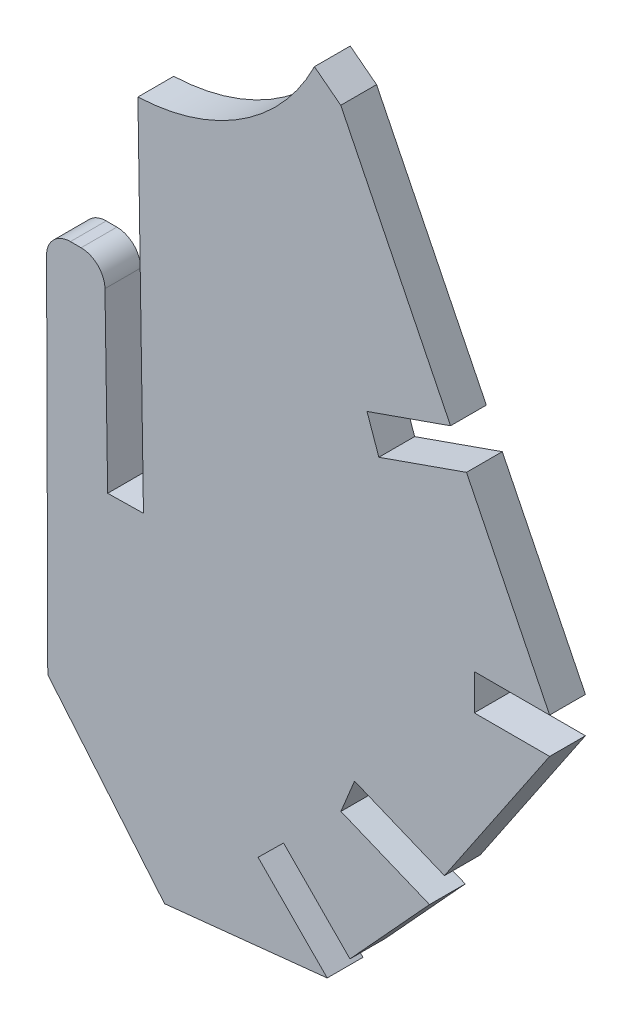
SolidWorks part; units mm, degrees
ref_plane "Front" through (0, 0, 0) normal (0, 0, 1) x (1, 0, 0)
ref_plane "Top" through (0, 0, 0) normal (0, 1, 0) x (1, 0, 0)
ref_plane "Right" through (0, 0, 0) normal (1, 0, 0) x (0, 0, -1)
sketch "Sketch1" plane through (0, 0, 0) normal (0, 0, 1) x (1, 0, 0)
  line L0 (1123.6821, 62.2264) -> (1123.2178, 92.2228)
  line L1 (1120.6824, 62.1799) -> (1123.6821, 62.2264)
  line L2 (1120.6824, 62.1799) -> (1120.4542, 76.9248)
  line L3 (1118.4545, 78.8938) -> (1117.5592, 78.8938)
  line L4 (1140.2234, 100.1224) -> (1149.4278, 81.4534)
  line L5 (1115.6596, 46.4993) -> (1125.4526, 34.7666)
  line L6 (1138.0165, 101.8227) -> (1140.2234, 100.1224)
  line L7 (1147.6618, 45.8093) -> (1140.993, 38.5296)
  line L8 (1135.4263, 44.1646) -> (1140.993, 38.5296)
  line L9 (1139.0868, 36.1905) -> (1133.2921, 42.0562)
  line L10 (1133.2921, 42.0562) -> (1135.4263, 44.1646)
  line L11 (1139.0868, 36.1905) -> (1125.4526, 34.7666)
  line L12 (1157.7351, 61.6037) -> (1151.4149, 61.6037)
  line L13 (1151.4149, 61.6037) -> (1151.4149, 64.6037)
  line L14 (1151.4149, 64.6037) -> (1157.7351, 64.6037)
  line L15 (1157.7351, 64.6037) -> (1150.7641, 78.743)
  line L16 (1157.7351, 61.6037) -> (1148.9148, 48.5379)
  line L17 (1115.6596, 46.4993) -> (1115.5592, 76.8872)
  line L18 (1139.7981, 67.9553) -> (1140.545, 63.2243) construction
  line L19 (1140.545, 63.2243) -> (1140.5295, 58.4929) construction
  line L20 (1140.5295, 58.4929) -> (1139.7981, 53.7613) construction
  line L21 (1139.7981, 53.7613) -> (1139.4494, 52.8563) construction
  line L22 (1139.4494, 52.8563) -> (1138.8421, 52.1969) construction
  line L23 (1138.8421, 52.1969) -> (1137.9708, 51.9417) construction
  line L24 (1137.9708, 51.9417) -> (1128.3194, 51.9417) construction
  line L25 (1128.3194, 51.9417) -> (1127.399, 52.191) construction
  line L26 (1127.399, 52.191) -> (1126.7425, 52.8447) construction
  line L27 (1126.7425, 52.8447) -> (1126.4921, 53.7613) construction
  line L28 (1126.4921, 53.7613) -> (1126.4921, 67.9553) construction
  line L29 (1126.4921, 67.9553) -> (1126.7425, 68.8719) construction
  line L30 (1126.7425, 68.8719) -> (1127.399, 69.5256) construction
  line L31 (1127.399, 69.5256) -> (1128.3194, 69.7749) construction
  line L32 (1128.3194, 69.7749) -> (1137.9708, 69.7749) construction
  line L33 (1137.9708, 69.7749) -> (1138.8391, 69.5191) construction
  line L34 (1138.8391, 69.5191) -> (1139.4435, 68.8588) construction
  line L35 (1139.4435, 68.8588) -> (1139.7981, 67.9553) construction
  line L36 (1141.3769, 51.634) -> (1148.9148, 48.5379)
  line L37 (1140.2371, 48.859) -> (1141.3769, 51.634)
  line L38 (1147.6618, 45.8093) -> (1140.2371, 48.859)
  line L39 (1149.4278, 81.4534) -> (1142.4234, 78.9944)
  line L40 (1142.4234, 78.9944) -> (1143.4171, 76.1638)
  line L41 (1143.4171, 76.1638) -> (1150.7641, 78.743)
  arc A0 (1123.2178, 92.2228) -> (1138.0165, 101.8227) centre (1122.5623, 109.4396) ccw
  arc A1 (1115.5592, 76.8872) -> (1117.5592, 78.8938) centre (1117.5592, 76.8938) cw
  arc A2 (1120.4542, 76.9248) -> (1118.4545, 78.8938) centre (1118.4545, 76.8938) ccw
  dimension "D17" = 2
  dimension "D1" = 3
  dimension "D2" = 3
  dimension "D3" = 90
  dimension "D4" = 90
  dimension "D5" = 90
  dimension "D6" = 90
  dimension "D7" = 3
  dimension "D8" = 90
  dimension "D9" = 90
  dimension "D10" = 3
  dimension "D11" = 3
  dimension "D12" = 90
  dimension "D13" = 90
  dimension "D14" = 90
  dimension "D15" = 90
  dimension "D16" = 30
  dimension "D18" = 15
extrude "Base-Extrude" add sketch "Sketch1" along normal blind 3
